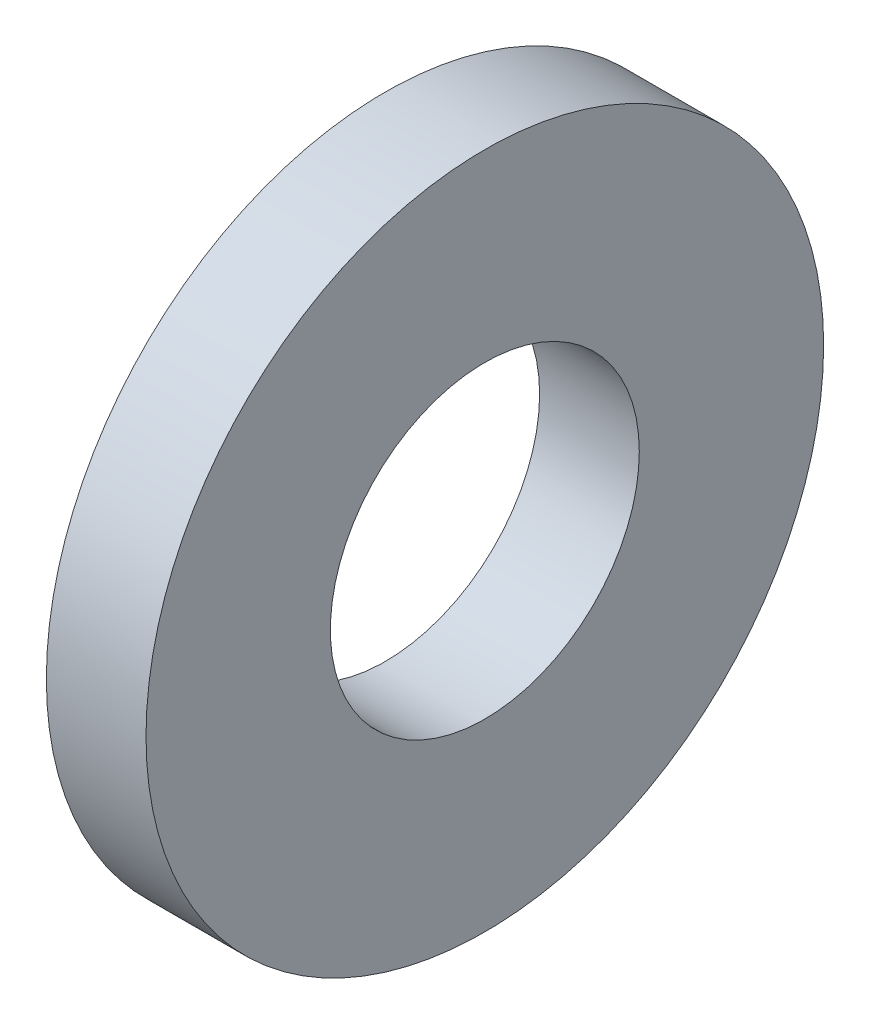
SolidWorks part; units mm, degrees
ref_plane "Plane1" through (0, 0, 0) normal (0, 0, 1) x (1, 0, 0)
ref_plane "Plane2" through (0, 0, 0) normal (0, 1, 0) x (1, 0, 0)
ref_plane "Plane3" through (0, 0, 0) normal (1, 0, 0) x (0, 0, -1)
sketch "Sketch1" plane through (0, 0, 0) normal (1, 0, 0) x (0, 0, -1)
  circle A0 centre (0, 0) radius 15.5
  circle A1 centre (0, 0) radius 34
  dimension "InsideDia" = 31
  dimension "OutsideDia" = 68
extrude "Base-Extrude" add sketch "Sketch1" along normal blind 10
